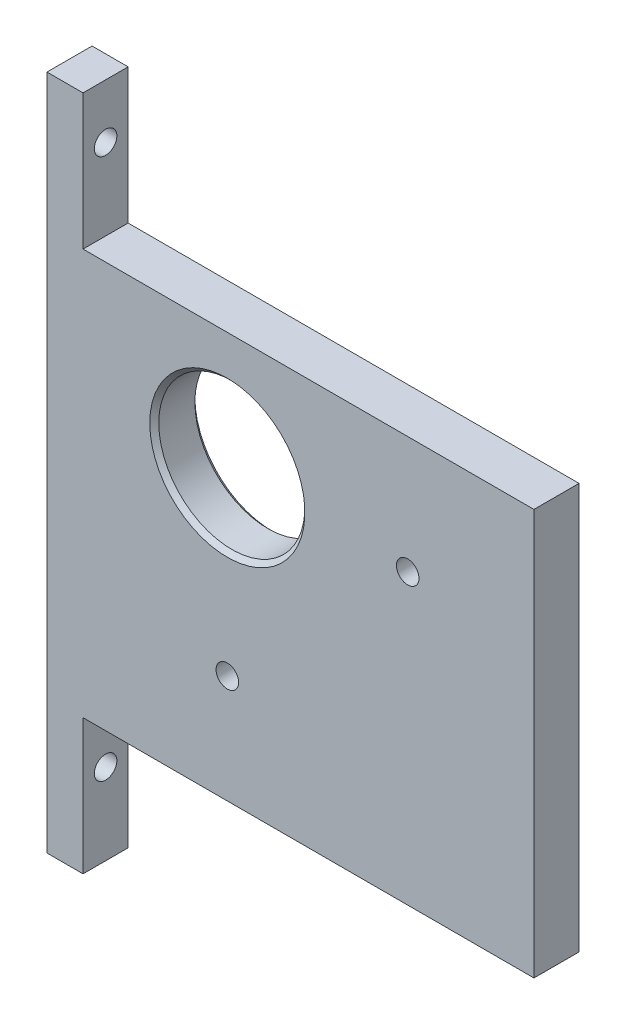
SolidWorks part; units mm, degrees
material "6063-T5"
ref_plane "前视基准面" through (0, 0, 0) normal (0, 0, 1) x (1, 0, 0)
ref_plane "上视基准面" through (0, 0, 0) normal (0, 1, 0) x (1, 0, 0)
ref_plane "右视基准面" through (0, 0, 0) normal (1, 0, 0) x (0, 0, -1)
sketch "草图1" plane through (0, 0, 0) normal (0, 0, 1) x (1, 0, 0)
  line L0 (4, 60) -> (4, 75)
  line L1 (0, 0) -> (4, 0)
  line L2 (0, 0) -> (0, 75)
  line L3 (0, 75) -> (4, 75)
  line L4 (4, 0) -> (4, 15)
  line L5 (4, 60) -> (70, 60)
  line L7 (4, 15) -> (70, 15)
  line L8 (70, 60) -> (70, 15)
  line L9 (60, 52.5) -> (60, 22.5) construction
  circle A0 centre (60, 52.5) radius 2.1 construction
  circle A1 centre (60, 22.5) radius 1.9862 construction
  circle A2 centre (20, 47) radius 8.1
  point P9 (0, 37.5)
  point P10 (70, 37.5)
  point P17 (60, 37.5)
  dimension "D5" = 28
  dimension "D6" = 20
  dimension "D7" = 16.2
  dimension "D8" = 4.2
  dimension "D9" = 30
  dimension "D10" = 10
  dimension "D1" = 4
  dimension "D2" = 75
  dimension "D3" = 45
  dimension "D4" = 70
extrude "凸台-拉伸1" add sketch "草图1" along normal blind 5
sketch "草图2" plane through (4, 0, 0) normal (1, 0, 0) x (0, 0, -1)
  line L0 (-5, 37.5) -> (0, 37.5) construction
  line L1 (-5, 15) -> (-5, 60) construction
  line L2 (0, 15) -> (0, 60) construction
  line L3 (-5, 75) -> (0, 75) construction
  line L5 (-5, 0) -> (0, 0) construction
  circle A0 centre (-2.5, 69) radius 1.25
  circle A1 centre (-2.5, 9) radius 1.25
  point P11 (-2.5, 37.5)
  dimension "D1" = 2.5
  dimension "D2" = 6
  dimension "D4" = 2.5
  dimension "D3" = 9
extrude "切除-拉伸1" cut sketch "草图2" against normal blind 5
sketch "草图3" plane through (0, 0, 0) normal (0, 0, -1) x (-1, 0, 0)
  line L0 (-70, 60) -> (-4, 60) construction
  circle A0 centre (-20, 47) radius 20 construction
  circle A1 centre (-40, 47) radius 1.25
  circle A2 centre (-20, 27) radius 1.25
  dimension "D1" = 40
  dimension "D2" = 2.5
  dimension "D3" = 13
extrude "切除-拉伸2" cut sketch "草图3" against normal blind 120
chamfer "倒角1" distance 0.5 angle 45 2 edges at (28.1, 47, 5) (28.1, 47, 0)
sketch "草图4" plane through (0, 0, 0) normal (0, 0, -1) x (-1, 0, 0)
  line L1 (-4, 15) -> (-70, 15) construction
  line L2 (-70, 60) -> (-54, 60)
  line L3 (-70, 60) -> (-70, 15)
  line L4 (-70, 15) -> (-54, 15)
  line L5 (-54, 60) -> (-54, 15)
  dimension "D1" = 16
extrude "切除-拉伸3" cut sketch "草图4" against normal blind 10
